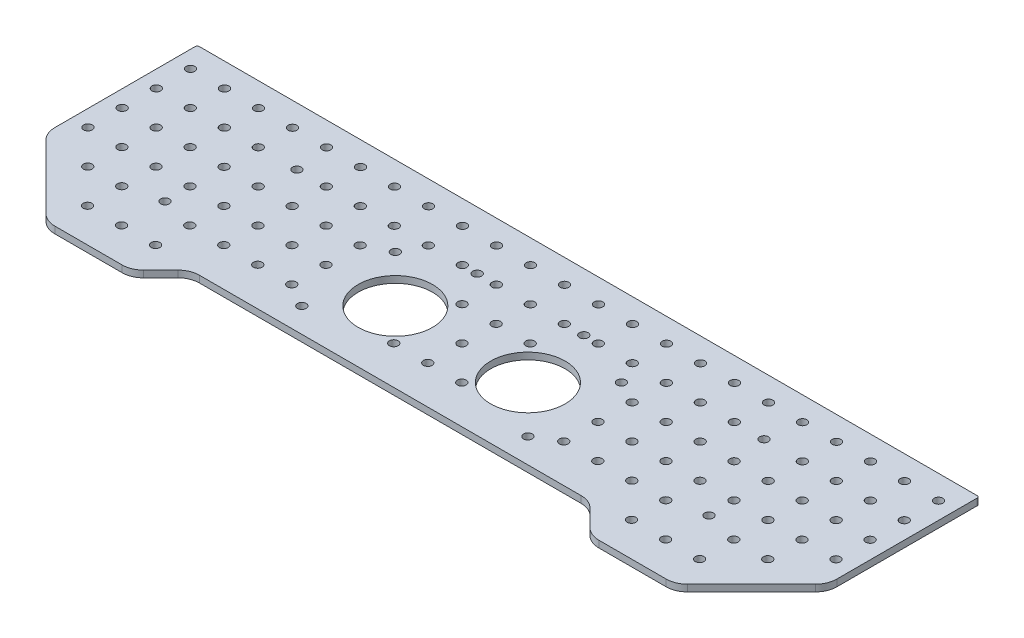
SolidWorks part; units mm, degrees
ref_plane "Front Plane" through (0, 0, 0) normal (0, 0, 1) x (1, 0, 0)
ref_plane "Top Plane" through (0, 0, 0) normal (0, 1, 0) x (1, 0, 0)
ref_plane "Right Plane" through (0, 0, 0) normal (1, 0, 0) x (0, 0, -1)
sketch "Sketch3" plane through (0, 0, 0) normal (0, 1, 0) x (1, 0, 0)
  line L0 (0, 0) -> (50000, 0) construction
  line L1 (184, -59.5875) -> (-184, -59.5875) construction
  line L2 (184, -59.5875) -> (184, 59.5875) construction
  line L3 (184, 59.5875) -> (-184, 59.5875) construction
  line L4 (-184, -59.5875) -> (-184, 59.5875) construction
  line L5 (184, -59.5875) -> (-184, 59.5875) construction
  line L6 (184, 59.5875) -> (-184, -59.5875) construction
  line L7 (0, 0) -> (0, -50000) construction
  line L8 (-141.9903, -11.5875) -> (49858.0097, -11.5875) construction
  line L9 (-130.2701, 7.3771) -> (-33.4655, 18.9646) construction
  line L10 (-128, -11.5875) -> (-31.1955, 0) construction
  line L11 (-125.7299, -30.5521) -> (-28.9254, -18.9646) construction
  line L12 (-49.1677, -33.5875) -> (49950.8323, -33.5875) construction
  line L13 (-47.419, -47.5875) -> (-50047.419, -47.5875) construction
  line L14 (-184, -11.5875) -> (-148, -47.5875)
  line L15 (-128, -11.5875) -> (-128, -50011.5875) construction
  line L16 (-148, -47.5875) -> (-108, -47.5875)
  line L17 (-94, -33.5875) -> (-108, -47.5875)
  line L18 (-94, -33.5875) -> (94, -33.5875)
  line L19 (-184, -11.5875) -> (-184, 59.5875)
  line L20 (-184, 59.5875) -> (184, 59.5875)
  line L21 (184, -11.5875) -> (184, 59.5875)
  line L22 (184, -11.5875) -> (148, -47.5875)
  line L23 (148, -47.5875) -> (108, -47.5875)
  line L24 (94, -33.5875) -> (108, -47.5875)
  line L26 (-15.1955, -16) -> (-47.1955, -16) construction
  line L27 (-15.1955, -16) -> (-15.1955, 16) construction
  line L28 (-15.1955, 16) -> (-47.1955, 16) construction
  line L29 (-47.1955, -16) -> (-47.1955, 16) construction
  line L30 (-15.1955, -16) -> (-47.1955, 16) construction
  line L31 (-15.1955, 16) -> (-47.1955, -16) construction
  line L32 (-9.1955, -22) -> (-53.1955, -22) construction
  line L33 (-9.1955, -22) -> (-9.1955, 22) construction
  line L34 (-9.1955, 22) -> (-53.1955, 22) construction
  line L35 (-53.1955, -22) -> (-53.1955, 22) construction
  line L36 (-9.1955, -22) -> (-53.1955, 22) construction
  line L37 (-9.1955, 22) -> (-53.1955, -22) construction
  circle A0 centre (-128, -11.5875) radius 48 construction
  circle A1 centre (-128, -11.5875) radius 19.1 construction
  circle A2 centre (-31.1955, 0) radius 19.1 construction
  arc A3 (-33.4655, 18.9646) -> (-28.9254, -18.9646) centre (-31.1955, 0) cw construction
  arc A4 (-130.2701, 7.3771) -> (-125.7299, -30.5521) centre (-128, -11.5875) ccw construction
  circle A5 centre (-128, -11.5875) radius 2.05
  circle A7 centre (128, -11.5875) radius 2.05
  circle A9 centre (-53.1955, 22) radius 2.05
  circle A10 centre (-53.1955, -22) radius 2.05
  circle A11 centre (53.1955, 22) radius 2.05
  circle A12 centre (53.1955, -22) radius 2.05
  circle A13 centre (-31.1955, 0) radius 17.5
  circle A14 centre (31.1955, 0) radius 17.5
  point P0 (0, 0)
  point P36 (0, 59.5875)
  point P40 (0, -33.5875)
  dimension "D4" = 96
  dimension "D6" = 38.2
  dimension "D12" = 4.1
  dimension "D15" = 35
  dimension "D1" = 368
  dimension "D2" = 119.175
  dimension "D3" = 48
  dimension "D5" = 56
  dimension "D8" = 26
  dimension "D9" = 12
  dimension "D10" = 45
  dimension "D11" = 45
  dimension "D13" = 32
  dimension "D14" = 44
extrude "Boss-Extrude2" add sketch "Sketch3" along normal blind 3.175
fillet "Fillet1" radius 10 8 edges at (184, 1.5875, 11.5875) (148, 1.5875, 47.5875) (108, 1.5875, 47.5875) (94, 1.5875, 33.5875) (-94, 1.5875, 33.5875) (-108, 1.5875, 47.5875) (-148, 1.5875, 47.5875) (-184, 1.5875, 11.5875)
fillet "Fillet2" radius 1 2 edges at (184, 1.5875, -59.5875) (-184, 1.5875, -59.5875)
sketch "Sketch5" plane through (0, 3.175, 0) normal (0, 1, 0) x (1, 0, 0)
  line L0 (0, 0) -> (0, -50000) construction
  circle A0 centre (-128, -11.5875) radius 48
  circle A1 centre (128, -11.5875) radius 48
  dimension "D1" = 96
sketch "Sketch6" plane through (0, 3.175, 0) normal (0, 1, 0) x (1, 0, 0)
  line L0 (0, 0) -> (0, -50000) construction
  line L1 (-160.014, 32.4127) -> (49839.986, 32.4127) construction
  line L2 (0, 0) -> (50000, 0) construction
  line L3 (21.2444, 56.4125) -> (50021.2444, 56.4125) construction
  line L4 (21.9898, 48.4125) -> (50021.9898, 48.4125) construction
  line L5 (183, 59.5875) -> (-183, 59.5875) construction
  line L6 (-176, 42.191) -> (-176, -49957.809) construction
  line L7 (-184, 58.5875) -> (-184, -7.4454) construction
  line L8 (-176, 48.4125) -> (-160, 48.4125) construction
  line L9 (-176, 48.4125) -> (-176.0869, 32.4127) construction
  circle A0 centre (-176, 48.4125) radius 2.05
  circle A1 centre (-160, 48.4125) radius 2.05
  circle A2 centre (-144, 48.4125) radius 2.05
  circle A3 centre (-128, 48.4125) radius 2.05
  circle A4 centre (-112, 48.4125) radius 2.05
  circle A5 centre (-96, 48.4125) radius 2.05
  circle A6 centre (-80, 48.4125) radius 2.05
  circle A7 centre (-64, 48.4125) radius 2.05
  circle A8 centre (-48, 48.4125) radius 2.05
  circle A9 centre (-32, 48.4125) radius 2.05
  circle A10 centre (-16, 48.4125) radius 2.05
  circle A11 centre (0, 48.4125) radius 2.05
  circle A12 centre (16, 48.4125) radius 2.05
  circle A13 centre (32, 48.4125) radius 2.05
  circle A14 centre (48, 48.4125) radius 2.05
  circle A15 centre (64, 48.4125) radius 2.05
  circle A16 centre (80, 48.4125) radius 2.05
  circle A17 centre (96, 48.4125) radius 2.05
  circle A18 centre (112, 48.4125) radius 2.05
  circle A19 centre (128, 48.4125) radius 2.05
  circle A20 centre (144, 48.4125) radius 2.05
  circle A21 centre (160, 48.4125) radius 2.05
  circle A22 centre (176, 48.4125) radius 2.05
  circle A23 centre (-160.0869, 32.4127) radius 2.05
  circle A24 centre (-144.0869, 32.4127) radius 2.05
  circle A25 centre (-128.0869, 32.4127) radius 2.05
  circle A26 centre (-112.0869, 32.4127) radius 2.05 construction
  circle A27 centre (-96.0869, 32.4127) radius 2.05
  circle A28 centre (-80.0869, 32.4127) radius 2.05
  circle A29 centre (-64.0869, 32.4127) radius 2.05
  circle A30 centre (-48.0869, 32.4127) radius 2.05
  circle A31 centre (-32.0869, 32.4127) radius 2.05
  circle A32 centre (-16.0869, 32.4127) radius 2.05
  circle A33 centre (-0.0869, 32.4127) radius 2.05
  circle A34 centre (15.9131, 32.4127) radius 2.05
  circle A35 centre (31.9131, 32.4127) radius 2.05
  circle A36 centre (47.9131, 32.4127) radius 2.05
  circle A37 centre (63.9131, 32.4127) radius 2.05
  circle A38 centre (79.9131, 32.4127) radius 2.05
  circle A39 centre (95.9131, 32.4127) radius 2.05
  circle A40 centre (111.9131, 32.4127) radius 2.05 construction
  circle A41 centre (127.9131, 32.4127) radius 2.05
  circle A42 centre (143.9131, 32.4127) radius 2.05
  circle A43 centre (159.9131, 32.4127) radius 2.05
  circle A44 centre (175.9131, 32.4127) radius 2.05
  circle A45 centre (-160.1738, 16.413) radius 2.05
  circle A46 centre (-144.1738, 16.413) radius 2.05
  circle A47 centre (-128.1738, 16.413) radius 2.05
  circle A48 centre (-112.1738, 16.413) radius 2.05
  circle A49 centre (-96.1738, 16.413) radius 2.05
  circle A50 centre (-80.1738, 16.413) radius 2.05
  circle A51 centre (-64.1738, 16.413) radius 2.05
  circle A52 centre (-48.1738, 16.413) radius 2.05 construction
  circle A53 centre (-32.1738, 16.413) radius 2.05 construction
  circle A54 centre (-16.1738, 16.413) radius 2.05
  circle A55 centre (-0.1738, 16.413) radius 2.05
  circle A56 centre (15.8262, 16.413) radius 2.05
  circle A57 centre (31.8262, 16.413) radius 2.05 construction
  circle A58 centre (47.8262, 16.413) radius 2.05 construction
  circle A59 centre (63.8262, 16.413) radius 2.05
  circle A60 centre (79.8262, 16.413) radius 2.05
  circle A61 centre (95.8262, 16.413) radius 2.05
  circle A62 centre (111.8262, 16.413) radius 2.05
  circle A63 centre (127.8262, 16.413) radius 2.05
  circle A64 centre (143.8262, 16.413) radius 2.05
  circle A65 centre (159.8262, 16.413) radius 2.05
  circle A66 centre (175.8262, 16.413) radius 2.05
  circle A67 centre (-160.2607, 0.4132) radius 2.05
  circle A68 centre (-144.2607, 0.4132) radius 2.05
  circle A69 centre (-128.2607, 0.4132) radius 2.05
  circle A70 centre (-112.2607, 0.4132) radius 2.05
  circle A71 centre (-96.2607, 0.4132) radius 2.05
  circle A72 centre (-80.2607, 0.4132) radius 2.05
  circle A73 centre (-64.2607, 0.4132) radius 2.05
  circle A74 centre (-48.2607, 0.4132) radius 2.05 construction
  circle A75 centre (-32.2607, 0.4132) radius 2.05 construction
  circle A76 centre (-16.2607, 0.4132) radius 2.05 construction
  circle A77 centre (-0.2607, 0.4132) radius 2.05
  circle A78 centre (15.7393, 0.4132) radius 2.05 construction
  circle A79 centre (31.7393, 0.4132) radius 2.05 construction
  circle A80 centre (47.7393, 0.4132) radius 2.05 construction
  circle A81 centre (63.7393, 0.4132) radius 2.05
  circle A82 centre (79.7393, 0.4132) radius 2.05
  circle A83 centre (95.7393, 0.4132) radius 2.05
  circle A84 centre (111.7393, 0.4132) radius 2.05
  circle A85 centre (127.7393, 0.4132) radius 2.05
  circle A86 centre (143.7393, 0.4132) radius 2.05
  circle A87 centre (159.7393, 0.4132) radius 2.05
  circle A88 centre (175.7393, 0.4132) radius 2.05
  circle A89 centre (-160.3476, -15.5866) radius 2.05
  circle A90 centre (-144.3476, -15.5866) radius 2.05
  circle A91 centre (-128.3476, -15.5866) radius 2.05 construction
  circle A92 centre (-112.3476, -15.5866) radius 2.05
  circle A93 centre (-96.3476, -15.5866) radius 2.05
  circle A94 centre (-80.3476, -15.5866) radius 2.05
  circle A95 centre (-64.3476, -15.5866) radius 2.05
  circle A96 centre (-48.3476, -15.5866) radius 2.05 construction
  circle A97 centre (-32.3476, -15.5866) radius 2.05 construction
  circle A98 centre (-16.3476, -15.5866) radius 2.05
  circle A99 centre (-0.3476, -15.5866) radius 2.05
  circle A100 centre (15.6524, -15.5866) radius 2.05
  circle A101 centre (31.6524, -15.5866) radius 2.05 construction
  circle A102 centre (47.6524, -15.5866) radius 2.05 construction
  circle A103 centre (63.6524, -15.5866) radius 2.05
  circle A104 centre (79.6524, -15.5866) radius 2.05
  circle A105 centre (95.6524, -15.5866) radius 2.05
  circle A106 centre (111.6524, -15.5866) radius 2.05
  circle A107 centre (127.6524, -15.5866) radius 2.05 construction
  circle A108 centre (143.6524, -15.5866) radius 2.05
  circle A109 centre (159.6524, -15.5866) radius 2.05
  circle A110 centre (175.6524, -15.5866) radius 2.05 construction
  circle A111 centre (-160.4345, -31.5863) radius 2.05 construction
  circle A112 centre (-144.4345, -31.5863) radius 2.05
  circle A113 centre (-128.4345, -31.5863) radius 2.05
  circle A114 centre (-112.4345, -31.5863) radius 2.05
  circle A115 centre (-96.4345, -31.5863) radius 2.05 construction
  circle A116 centre (-80.4345, -31.5863) radius 2.05 construction
  circle A117 centre (-64.4345, -31.5863) radius 2.05 construction
  circle A118 centre (-48.4345, -31.5863) radius 2.05 construction
  circle A119 centre (-32.4345, -31.5863) radius 2.05 construction
  circle A120 centre (-16.4345, -31.5863) radius 2.05 construction
  circle A121 centre (-0.4345, -31.5863) radius 2.05 construction
  circle A122 centre (15.5655, -31.5863) radius 2.05 construction
  circle A123 centre (31.5655, -31.5863) radius 2.05 construction
  circle A124 centre (47.5655, -31.5863) radius 2.05 construction
  circle A125 centre (63.5655, -31.5863) radius 2.05 construction
  circle A126 centre (79.5655, -31.5863) radius 2.05 construction
  circle A127 centre (95.5655, -31.5863) radius 2.05 construction
  circle A128 centre (111.5655, -31.5863) radius 2.05
  circle A129 centre (127.5655, -31.5863) radius 2.05
  circle A130 centre (143.5655, -31.5863) radius 2.05
  circle A131 centre (159.5655, -31.5863) radius 2.05 construction
  circle A132 centre (175.5655, -31.5863) radius 2.05 construction
  circle A133 centre (-160.5214, -47.5861) radius 2.05 construction
  circle A134 centre (-144.5214, -47.5861) radius 2.05 construction
  circle A135 centre (-128.5214, -47.5861) radius 2.05 construction
  circle A136 centre (-112.5214, -47.5861) radius 2.05 construction
  circle A137 centre (-96.5214, -47.5861) radius 2.05 construction
  circle A138 centre (-80.5214, -47.5861) radius 2.05 construction
  circle A139 centre (-64.5214, -47.5861) radius 2.05 construction
  circle A140 centre (-48.5214, -47.5861) radius 2.05 construction
  circle A141 centre (-32.5214, -47.5861) radius 2.05 construction
  circle A142 centre (-16.5214, -47.5861) radius 2.05 construction
  circle A143 centre (-0.5214, -47.5861) radius 2.05 construction
  circle A144 centre (15.4786, -47.5861) radius 2.05 construction
  circle A145 centre (31.4786, -47.5861) radius 2.05 construction
  circle A146 centre (47.4786, -47.5861) radius 2.05 construction
  circle A147 centre (63.4786, -47.5861) radius 2.05 construction
  circle A148 centre (79.4786, -47.5861) radius 2.05 construction
  circle A149 centre (95.4786, -47.5861) radius 2.05 construction
  circle A150 centre (111.4786, -47.5861) radius 2.05 construction
  circle A151 centre (127.4786, -47.5861) radius 2.05 construction
  circle A152 centre (143.4786, -47.5861) radius 2.05 construction
  circle A153 centre (159.4786, -47.5861) radius 2.05 construction
  circle A154 centre (175.4786, -47.5861) radius 2.05 construction
  circle A155 centre (-176.0869, 32.4127) radius 2.05
  circle A156 centre (-176.1738, 16.413) radius 2.05
  circle A157 centre (-176.2607, 0.4132) radius 2.05
  circle A158 centre (-176.3476, -15.5866) radius 2.05 construction
  circle A159 centre (-176.4345, -31.5863) radius 2.05 construction
  circle A160 centre (-176.5214, -47.5861) radius 2.05 construction
  circle A161 centre (-25.0869, 32.4127) radius 2.05
  circle A162 centre (25.0869, 32.4127) radius 2.05
  circle A163 centre (109.9131, 32.4127) radius 2.05
  circle A164 centre (-109.9131, 32.4127) radius 2.05
  dimension "D4" = 4.1
  dimension "D1" = 8
  dimension "D2" = 3.175
  dimension "D3" = 8
  dimension "D7" = 16
  dimension "D8" = 16
  dimension "D9" = 23.9131
  dimension "D10" = 135
  dimension "D11" = 270
  dimension "D5" = 23
  dimension "D6" = 7
extrude "Cut-Extrude3" cut sketch "Sketch6" against normal blind 3.18
equation "\"wheelDiameter\"= 96mm"
equation "\"thick\"= 3.175mm"
equation "\"sh\"= 4.1mm"
equation "\"w\"= 368mm"
equation "\"h\"= \"wheelDiameter\" + 20mm + 3.175mm"
equation "\"pitchDiameter\"= 38.2mm"
equation "\"D1@Sketch3\"=\"w\""
equation "\"D2@Sketch3\"=\"h\""
equation "\"D3@Sketch3\"=\"wheelDiameter\"/2"
equation "\"D4@Sketch3\"=\"wheelDiameter\""
equation "\"D5@Sketch3\"=\"wheelDiameter\"/2 +8"
equation "\"D6@Sketch3\"=\"pitchDiameter\""
equation "\"beltPitch\"= 315mm"
equation "\"D7@Sketch3\"=\"beltPitch\""
equation "\"D12@Sketch3\"=\"sh\""
equation "\"D1@Boss-Extrude2\"=\"thick\""
equation "\"D1@Sketch5\"=\"wheelDiameter\""
equation "\"D2@Sketch6\"=\"thick\""
equation "\"D4@Sketch6\"=\"sh\""
